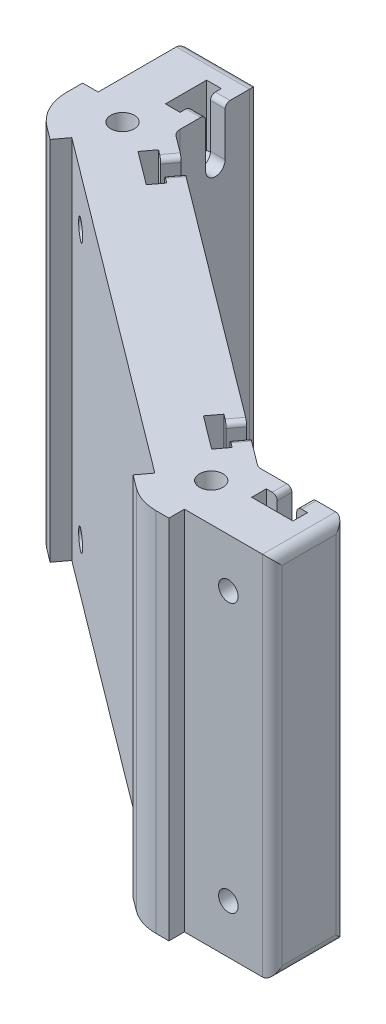
SolidWorks part; units mm, degrees
ref_plane "Front Plane" through (0, 0, 0) normal (0, 0, 1) x (1, 0, 0)
ref_plane "Top Plane" through (0, 0, 0) normal (0, 1, 0) x (1, 0, 0)
ref_plane "Right Plane" through (0, 0, 0) normal (1, 0, 0) x (0, 0, -1)
sketch "Sketch1" plane through (0, 0, 0) normal (0, 1, 0) x (1, 0, 0)
  line L0 (0, -10) -> (0, -6.825) construction
  line L2 (20.6667, -6.825) -> (20.6667, 62) construction
  line L3 (-6, -8) -> (-4.095, -5.46) construction
  line L6 (-4.095, -5.46) -> (0, 0) construction
  line L7 (0, -10) -> (-3.3333, -10) construction
  line L8 (0, 0) -> (0, -6.825) construction
  line L9 (-3.1623, -9.4868) -> (0, 0) construction
  line L10 (0, 0) -> (20.6667, 62) construction
  line L12 (-11.6283, 18.94) -> (2.725, 8.175)
  line L13 (20.6667, -6.825) -> (20.6667, 8.175)
  line L14 (20.6667, 8.175) -> (2.725, 8.175)
  line L15 (-6, -8) -> (-8.6667, -6)
  line L16 (-8.6667, -6) -> (-6.7617, -3.46)
  line L17 (0, -10) -> (2.6667, -10)
  line L18 (2.6667, -10) -> (2.6667, -6.825)
  line L19 (-74.7617, 47.54) -> (-6.7617, -3.46)
  line L20 (-6.7617, -3.46) -> (-4.095, -5.46) construction
  line L21 (0, -6.825) -> (2.6667, -6.825) construction
  line L22 (2.6667, -6.825) -> (20.6667, -6.825)
  line L23 (-6, -8) -> (-79.3333, 47) construction
  line L24 (-3.3333, -10) -> (-6, -8) construction
  line L25 (-8.6667, -6) -> (-83.3333, 50) construction
  line L26 (-74.7617, 47.54) -> (-76.6667, 45)
  line L27 (-76.6667, 45) -> (-79.3333, 47)
  line L28 (-83.3333, 50) -> (-83.3333, 76.3333) construction
  line L29 (-83.3333, 55) -> (-83.3333, 58.3333)
  line L30 (-83.3333, 58.3333) -> (-80.1583, 58.3333)
  line L31 (-80.1583, 58.3333) -> (-80.1583, 76.3333)
  line L32 (20.6667, 62) -> (-20.6283, 6.94) construction
  line L33 (-80.1583, 76.3333) -> (-65.1583, 76.3333)
  line L34 (-65.1583, 76.3333) -> (-65.1583, 59.0875)
  line L35 (-82.2776, 50.5279) -> (-65.1583, 59.0875) construction
  line L36 (-65.1583, 59.0875) -> (-51.3617, 48.74)
  line L37 (-51.3617, 48.74) -> (-60.3617, 36.74) construction
  line L38 (-51.3617, 48.74) -> (-11.6283, 18.94)
  line L39 (-83.3333, 76.3333) -> (-80.1583, 76.3333) construction
  arc A0 (0, -10) -> (-6, -8) centre (0, 0) cw
  arc A1 (-83.3333, 55) -> (-79.3333, 47) centre (-73.3333, 55) ccw
  dimension "D1" = 10
  dimension "D3" = 60
  dimension "D7" = 3.3333
  dimension "D2" = 3.175
  dimension "D4" = 18
  dimension "D5" = 15
  dimension "D6" = 2.6667
extrude "Boss-Extrude1" add sketch "Sketch1" along normal blind 75
sketch "Sketch2" plane through (0, 0, 6.825) normal (0, 0, 1) x (1, 0, 0)
  line L0 (11.6667, 0) -> (11.6667, 75) construction
  line L1 (2.6667, 0) -> (20.6667, 0) construction
  line L2 (2.6667, 75) -> (20.6667, 75) construction
  circle A0 centre (11.6667, 10) radius 2
  circle A1 centre (11.6667, 65) radius 2
  dimension "D1" = 4
  dimension "D2" = 10
  dimension "D3" = 10
extrude "Cut-Extrude1" cut sketch "Sketch2" against normal up to surface (15 mm away) up to face at (11.6958, 37.5, -8.175)
sketch "Sketch3" plane through (-4.095, 0, 5.46) normal (-0.6, 0, 0.8) x (0.8, 0, 0.6)
  line L0 (-12.3333, 0) -> (-12.3333, 75) construction
  line L1 (-88.3333, 0) -> (-3.3333, 0) construction
  line L2 (-88.3333, 75) -> (-3.3333, 75) construction
  line L3 (-3.3333, 75) -> (-3.3333, 0) construction
  line L4 (-45.8333, 0) -> (-45.8333, 75) construction
  line L5 (-88.3333, 0) -> (-3.3333, 0) construction
  line L6 (-88.3333, 75) -> (-3.3333, 75) construction
  circle A0 centre (-12.3333, 10) radius 2
  circle A1 centre (-12.3333, 65) radius 2
  circle A2 centre (-79.3333, 10) radius 2
  circle A3 centre (-79.3333, 65) radius 2
  point P22 (-10.5, 0)
  point P23 (-10.5, 70)
  point P24 (0, 0)
  point P25 (0, 0)
  dimension "D1" = 4
  dimension "D3" = 10
  dimension "D2" = 10
  dimension "D4" = 9
extrude "Cut-Extrude2" cut sketch "Sketch3" against normal up to surface (15 mm away) up to face at (-31.2167, 37.5, -33.6313)
sketch "Sketch4" plane through (-80.1583, 0, 0) normal (-1, 0, 0) x (0, 0, 1)
  line L0 (-67.3333, 0) -> (-67.3333, 75) construction
  line L1 (-76.3333, 0) -> (-58.3333, 0) construction
  line L2 (-76.3333, 75) -> (-58.3333, 75) construction
  circle A0 centre (-67.3333, 10) radius 2
  circle A1 centre (-67.3333, 65) radius 2
  dimension "D1" = 4
  dimension "D2" = 10
  dimension "D3" = 10
extrude "Cut-Extrude3" cut sketch "Sketch4" against normal up to surface (15 mm away) up to face at (-65.1583, 37.5, -67.7104)
sketch "Sketch6" plane through (4.905, 0, -6.54) normal (0.6, 0, -0.8) x (-0.8, 0, -0.6)
  line L0 (8.1146, 62.5643) -> (12.3333, 60.1286)
  line L1 (12.3333, 60.1286) -> (16.5521, 62.5643) construction
  line L2 (16.5521, 62.5643) -> (16.5521, 67.4357) construction
  line L3 (16.5521, 67.4357) -> (12.3333, 69.8714) construction
  line L4 (12.3333, 69.8714) -> (8.1146, 67.4357) construction
  line L5 (8.1146, 67.4357) -> (8.1146, 62.5643) construction
  line L6 (8.1146, 62.5643) -> (12.3333, 60.1286) construction
  line L7 (12.3333, 5.1286) -> (16.5521, 7.5643) construction
  line L8 (16.5521, 7.5643) -> (16.5521, 12.4357) construction
  line L9 (16.5521, 12.4357) -> (12.3333, 14.8714) construction
  line L10 (12.3333, 14.8714) -> (8.1146, 12.4357) construction
  line L11 (8.1146, 12.4357) -> (8.1146, 7.5643) construction
  line L12 (8.1146, 7.5643) -> (12.3333, 5.1286) construction
  line L13 (79.3333, 5.1286) -> (83.5521, 7.5643) construction
  line L14 (83.5521, 7.5643) -> (83.5521, 12.4357) construction
  line L15 (83.5521, 12.4357) -> (79.3333, 14.8714) construction
  line L16 (79.3333, 14.8714) -> (75.1146, 12.4357) construction
  line L17 (75.1146, 12.4357) -> (75.1146, 7.5643) construction
  line L18 (75.1146, 7.5643) -> (79.3333, 5.1286) construction
  line L19 (79.3333, 60.1286) -> (83.5521, 62.5643) construction
  line L20 (83.5521, 62.5643) -> (83.5521, 67.4357) construction
  line L21 (83.5521, 67.4357) -> (79.3333, 69.8714) construction
  line L22 (79.3333, 69.8714) -> (75.1146, 67.4357) construction
  line L23 (75.1146, 67.4357) -> (75.1146, 62.5643) construction
  line L24 (75.1146, 62.5643) -> (79.3333, 60.1286) construction
  line L25 (12.3333, 60.1286) -> (16.5521, 62.5643)
  line L26 (16.5521, 62.5643) -> (16.5521, 75)
  line L27 (2.725, 75) -> (87.5792, 75) construction
  line L28 (16.5521, 75) -> (8.1146, 75)
  line L29 (8.1146, 75) -> (8.1146, 62.5643)
  line L30 (75.1146, 62.5643) -> (79.3333, 60.1286)
  line L31 (79.3333, 60.1286) -> (83.5521, 62.5643)
  line L32 (83.5521, 62.5643) -> (83.5521, 75)
  line L33 (83.5521, 75) -> (75.1146, 75)
  line L34 (75.1146, 75) -> (75.1146, 62.5643)
  line L35 (8.1146, 12.4357) -> (12.3333, 14.8714)
  line L36 (12.3333, 14.8714) -> (16.5521, 12.4357)
  line L37 (16.5521, 12.4357) -> (16.5521, 0)
  line L38 (2.725, 0) -> (87.5792, 0) construction
  line L39 (16.5521, 0) -> (8.1146, 0)
  line L40 (8.1146, 0) -> (8.1146, 12.4357)
  line L41 (75.1146, 12.4357) -> (79.3333, 14.8714)
  line L42 (79.3333, 14.8714) -> (83.5521, 12.4357)
  line L43 (83.5521, 12.4357) -> (83.5521, 0)
  line L44 (83.5521, 0) -> (75.1146, 0)
  line L45 (75.1146, 0) -> (75.1146, 12.4357)
  circle A0 centre (12.3333, 65) radius 4.2187 construction
  circle A1 centre (12.3333, 10) radius 4.2188 construction
  circle A2 centre (79.3333, 10) radius 4.2187 construction
  circle A3 centre (79.3333, 65) radius 4.2187 construction
  dimension "D1" = 8.4375
extrude "Cut-Extrude5" cut sketch "Sketch6" against normal blind 3 from offset 3 offset against normal yes
sketch "Sketch7" plane through (4.905, 0, -6.54) normal (0.6, 0, -0.8) x (-0.8, 0, -0.6)
  line L0 (14.3333, 65) -> (14.3333, 75)
  line L1 (2.725, 75) -> (87.5792, 75) construction
  line L2 (14.3333, 75) -> (10.3333, 75)
  line L3 (10.3333, 75) -> (10.3333, 65)
  line L4 (81.3333, 65) -> (81.3333, 75)
  line L5 (81.3333, 0) -> (77.3333, 0)
  line L6 (2.725, 37.5) -> (87.5792, 37.5) construction
  line L7 (2.725, 75) -> (2.725, 0) construction
  line L8 (87.5792, 75) -> (87.5792, 0) construction
  line L18 (81.3333, 75) -> (77.3333, 75)
  line L19 (77.3333, 75) -> (77.3333, 65)
  line L20 (81.3333, 10) -> (81.3333, 0)
  line L21 (77.3333, 0) -> (77.3333, 10)
  line L22 (14.3333, 0) -> (10.3333, 0)
  line L23 (14.3333, 10) -> (14.3333, 0)
  line L24 (10.3333, 0) -> (10.3333, 10)
  arc A0 (10.3333, 65) -> (14.3333, 65) centre (12.3333, 65) cw
  circle A1 centre (12.3333, 65) radius 2 construction
  arc A5 (77.3333, 65) -> (81.3333, 65) centre (79.3333, 65) cw
  circle A6 centre (79.3333, 65) radius 2 construction
  arc A7 (77.3333, 10) -> (81.3333, 10) centre (79.3333, 10) ccw
  arc A8 (10.3333, 10) -> (14.3333, 10) centre (12.3333, 10) ccw
extrude "Cut-Extrude6" cut sketch "Sketch7" against normal blind 3
sketch "Sketch8" plane through (0, 0, -8.175) normal (0, 0, -1) x (-1, 0, 0)
  line L0 (-15.8854, 0) -> (-15.8854, 12.4357)
  line L1 (-11.6667, 60.1286) -> (-7.4479, 62.5643) construction
  line L2 (-7.4479, 62.5643) -> (-7.4479, 67.4357) construction
  line L3 (-7.4479, 67.4357) -> (-11.6667, 69.8714) construction
  line L4 (-11.6667, 69.8714) -> (-15.8854, 67.4357) construction
  line L5 (-15.8854, 67.4357) -> (-15.8854, 62.5643) construction
  line L6 (-15.8854, 62.5643) -> (-11.6667, 60.1286) construction
  line L7 (-11.6667, 5.1286) -> (-7.4479, 7.5643) construction
  line L8 (-7.4479, 7.5643) -> (-7.4479, 12.4357) construction
  line L9 (-7.4479, 12.4357) -> (-11.6667, 14.8714) construction
  line L10 (-11.6667, 14.8714) -> (-15.8854, 12.4357) construction
  line L11 (-15.8854, 12.4357) -> (-15.8854, 7.5643) construction
  line L12 (-15.8854, 7.5643) -> (-11.6667, 5.1286) construction
  line L13 (-20.6667, 0) -> (-2.725, 0) construction
  line L14 (-15.8854, 12.4357) -> (-11.6667, 14.8714)
  line L15 (-11.6667, 14.8714) -> (-7.4479, 12.4357)
  line L16 (-7.4479, 12.4357) -> (-7.4479, 0)
  line L17 (-7.4479, 0) -> (-15.8854, 0)
  line L18 (-15.8854, 62.5643) -> (-11.6667, 60.1286)
  line L19 (-11.6667, 60.1286) -> (-7.4479, 62.5643)
  line L20 (-7.4479, 62.5643) -> (-7.4479, 75)
  line L21 (-20.6667, 75) -> (-2.725, 75) construction
  line L22 (-7.4479, 75) -> (-15.8854, 75)
  line L23 (-15.8854, 75) -> (-15.8854, 62.5643)
  circle A0 centre (-11.6667, 65) radius 4.2187 construction
  circle A1 centre (-11.6667, 10) radius 4.2188 construction
  dimension "D1" = 8.4375
extrude "Cut-Extrude7" cut sketch "Sketch8" against normal blind 3 from offset 3 offset against normal yes
sketch "Sketch9" plane through (0, 0, -8.175) normal (0, 0, -1) x (-1, 0, 0)
  line L0 (-9.6667, 65) -> (-9.6667, 75)
  line L1 (-20.6667, 75) -> (-2.725, 75) construction
  line L2 (-9.6667, 75) -> (-13.6667, 75)
  line L3 (-13.6667, 75) -> (-13.6667, 65)
  line L4 (-13.6667, 10) -> (-13.6667, 0)
  line L5 (-20.6667, 0) -> (-2.725, 0) construction
  line L6 (-13.6667, 0) -> (-9.6667, 0)
  line L7 (-9.6667, 0) -> (-9.6667, 10)
  arc A0 (-13.6667, 65) -> (-9.6667, 65) centre (-11.6667, 65) cw
  circle A1 centre (-11.6667, 65) radius 2 construction
  arc A2 (-13.6667, 10) -> (-9.6667, 10) centre (-11.6667, 10) ccw
  circle A3 centre (-11.6667, 10) radius 2 construction
extrude "Cut-Extrude8" cut sketch "Sketch9" against normal blind 3
sketch "Sketch10" plane through (-65.1583, 0, 0) normal (1, 0, 0) x (0, 0, -1)
  line L0 (63.1146, 62.5643) -> (67.3333, 60.1286)
  line L1 (67.3333, 60.1286) -> (71.5521, 62.5643) construction
  line L2 (71.5521, 62.5643) -> (71.5521, 67.4357) construction
  line L3 (71.5521, 67.4357) -> (67.3333, 69.8714) construction
  line L4 (67.3333, 69.8714) -> (63.1146, 67.4357) construction
  line L5 (63.1146, 67.4357) -> (63.1146, 62.5643) construction
  line L6 (63.1146, 62.5643) -> (67.3333, 60.1286) construction
  line L7 (67.3333, 5.1286) -> (71.5521, 7.5643) construction
  line L8 (71.5521, 7.5643) -> (71.5521, 12.4357) construction
  line L9 (71.5521, 12.4357) -> (67.3333, 14.8714) construction
  line L10 (67.3333, 14.8714) -> (63.1146, 12.4357) construction
  line L11 (63.1146, 12.4357) -> (63.1146, 7.5643) construction
  line L12 (63.1146, 7.5643) -> (67.3333, 5.1286) construction
  line L13 (67.3333, 60.1286) -> (71.5521, 62.5643)
  line L14 (71.5521, 62.5643) -> (71.5521, 75)
  line L15 (59.0875, 75) -> (76.3333, 75) construction
  line L16 (71.5521, 75) -> (63.1146, 75)
  line L17 (63.1146, 75) -> (63.1146, 62.5643)
  line L18 (63.1146, 12.4357) -> (67.3333, 14.8714)
  line L19 (67.3333, 14.8714) -> (71.5521, 12.4357)
  line L20 (71.5521, 12.4357) -> (71.5521, 0)
  line L21 (59.0875, 0) -> (76.3333, 0) construction
  line L22 (71.5521, 0) -> (63.1146, 0)
  line L23 (63.1146, 0) -> (63.1146, 12.4357)
  circle A0 centre (67.3333, 65) radius 4.2188 construction
  circle A1 centre (67.3333, 10) radius 4.2188 construction
  dimension "D1" = 8.4375
extrude "Cut-Extrude9" cut sketch "Sketch10" against normal blind 3 from offset 3 offset against normal yes
sketch "Sketch5" plane through (0, 75, 0) normal (0, 1, 0) x (1, 0, 0)
  line L0 (-3.1623, -9.4868) -> (2.725, 8.175) construction
  line L1 (-82.2776, 50.5279) -> (-65.1583, 59.0875) construction
  line L2 (-72.3333, 55.5) -> (0.3333, 1) construction
  line L3 (-74.7617, 47.54) -> (-6.7617, -3.46) construction
  line L4 (-8.6667, -6) -> (-6, -8) construction
  arc A0 (-6, -8) -> (0, -10) centre (0, 0) ccw construction
  arc A1 (-83.3333, 55) -> (-79.3333, 47) centre (-73.3333, 55) ccw construction
  circle A2 centre (0.3333, 1) radius 2.413
  circle A3 centre (-72.3333, 55.5) radius 2.413
  dimension "D1" = 4.826
  dimension "D2" = 11
extrude "Cut-Extrude4" cut sketch "Sketch5" against normal blind 6.35 draft 8 contours A2 | A3
sketch "Sketch11" plane through (-65.1583, 0, 0) normal (1, 0, 0) x (0, 0, -1)
  line L0 (69.3333, 65) -> (69.3333, 75)
  line L1 (59.0875, 75) -> (76.3333, 75) construction
  line L2 (69.3333, 75) -> (65.3333, 75)
  line L3 (65.3333, 75) -> (65.3333, 65)
  line L4 (69.3333, 10) -> (69.3333, 0)
  line L5 (59.0875, 0) -> (76.3333, 0) construction
  line L6 (69.3333, 0) -> (65.3333, 0)
  line L7 (65.3333, 0) -> (65.3333, 10)
  arc A0 (65.3333, 65) -> (69.3333, 65) centre (67.3333, 65) cw
  circle A1 centre (67.3333, 65) radius 2 construction
  arc A2 (65.3333, 10) -> (69.3333, 10) centre (67.3333, 10) ccw
  circle A3 centre (67.3333, 10) radius 2 construction
extrude "Cut-Extrude10" cut sketch "Sketch11" against normal blind 3
sketch "Sketch14" plane through (0, 68.65, 0) normal (0, 1, 0) x (1, 0, 0)
  circle A0 centre (-72.3333, 55.5) radius 1.5206
  circle A1 centre (0.3333, 1) radius 1.5206
  circle A2 centre (-72.3333, 55.5) radius 1.5206 construction
extrude "Cut-Extrude12" cut sketch "Sketch14" against normal blind 5
ref_plane "Plane1" through (0, 37.5, 0) normal (0, 1, 0) x (1, 0, 0)
mirror "Mirror1" about plane through (0, 37.5, 0) normal (0, 1, 0) of "Cut-Extrude4", "Cut-Extrude12"
fillet "Fillet1" radius 1 16 edges at (-66.6583, 75, -69.3333) (-66.6583, 75, -65.3333) (-57.8617, 75, -51.74) (-61.0617, 75, -54.14) (-66.6583, 0, -69.3333) (-66.6583, 0, -65.3333) (-61.0617, 0, -54.14) (-57.8617, 0, -51.74) (-7.4617, 0, -13.94) (-4.2617, 0, -11.54) (13.6667, 0, -6.675) (9.6667, 0, -6.675) (-7.4617, 75, -13.94) (-4.2617, 75, -11.54) (9.6667, 75, -6.675) (13.6667, 75, -6.675)
fillet "Fillet2" radius 2 10 edges at (20.6667, 75, -0.675) (-72.6583, 75, -76.3333) (-72.6583, 0, -76.3333) (20.6667, 0, -0.675) (-80.1583, 37.5, -76.3333) (-65.1583, 37.5, -76.3333) (-65.1583, 37.5, -59.0875) (2.725, 37.5, -8.175) (20.6667, 37.5, -8.175) (20.6667, 37.5, 6.825)
equation "\"0.25i\"=3"
